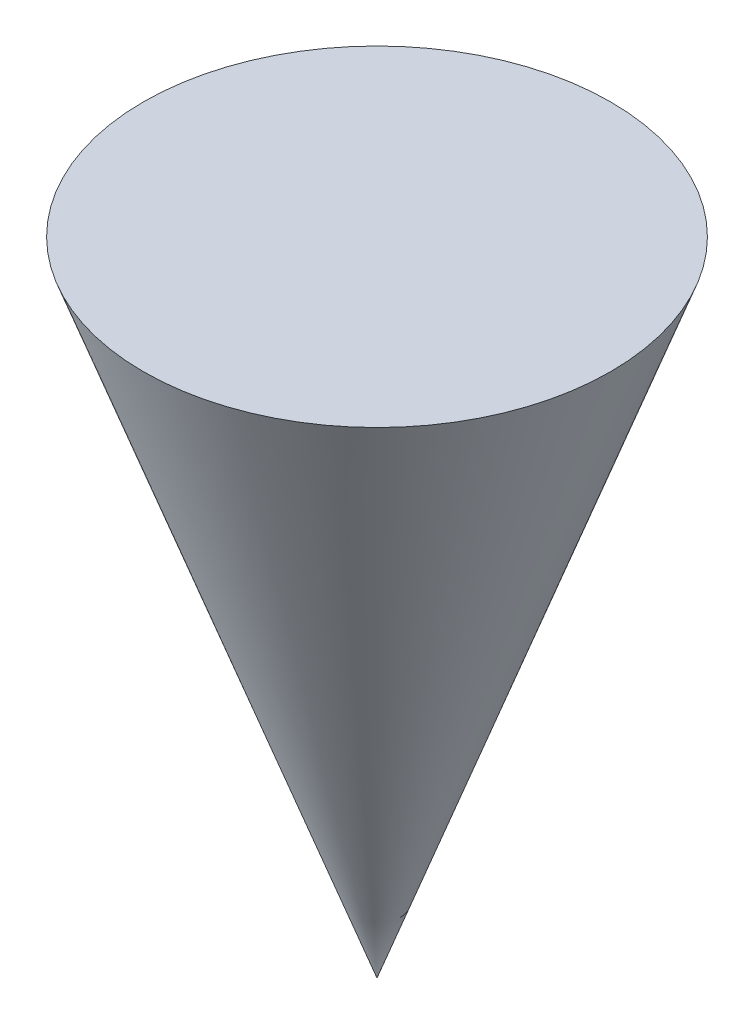
SolidWorks part; units mm, degrees
ref_plane "Front Plane" through (0, 0, 0) normal (0, 0, 1) x (1, 0, 0)
ref_plane "Top Plane" through (0, 0, 0) normal (0, 1, 0) x (1, 0, 0)
ref_plane "Right Plane" through (0, 0, 0) normal (1, 0, 0) x (0, 0, -1)
sketch "Sketch1" plane through (0, 0, 0) normal (0, 0, 1) x (1, 0, 0)
  line L0 (0, 0) -> (-36.397, 100)
  line L1 (-36.397, 100) -> (36.397, 100)
  line L2 (36.397, 100) -> (0, 0)
  line L3 (0, 0) -> (0, 100) construction
  dimension "D1" = 40
  dimension "D2" = 100
revolve "Revolve1" add sketch "Sketch1" angle 360 about L3
